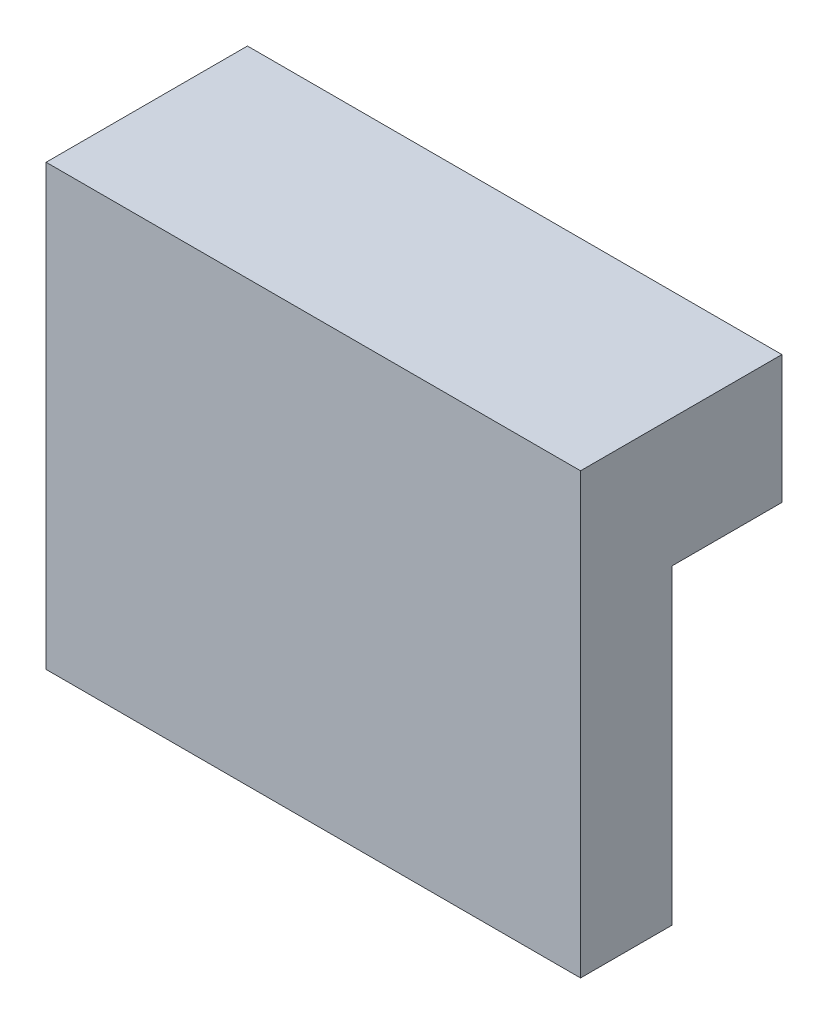
SolidWorks part; units mm, degrees
ref_plane "前视基准面" through (0, 0, 0) normal (0, 0, 1) x (1, 0, 0)
ref_plane "上视基准面" through (0, 0, 0) normal (0, 1, 0) x (1, 0, 0)
ref_plane "右视基准面" through (0, 0, 0) normal (1, 0, 0) x (0, 0, -1)
sketch "草图1" plane through (0, 0, 0) normal (0, 0, 1) x (1, 0, 0)
  line L1 (-73, 60) -> (73, 60)
  line L2 (-73, 60) -> (-73, -60)
  line L3 (-73, -60) -> (73, -60)
  line L4 (73, 60) -> (73, -60)
  line L5 (-73, 60) -> (73, -60) construction
  line L6 (-73, -60) -> (73, 60) construction
  point P0 (0, 0)
  dimension "D1" = 146
  dimension "D2" = 120
extrude "凸台-拉伸1" add sketch "草图1" along normal mid plane 25
sketch "草图2" plane through (0, 0, -12.5) normal (0, 0, -1) x (-1, 0, 0)
  line L0 (73, 60) -> (73, -60) construction
  line L1 (-73, 60) -> (73, 60)
  line L2 (-73, 60) -> (-73, 25)
  line L3 (-73, 25) -> (73, 25)
  line L4 (73, 60) -> (73, 25)
  dimension "D1" = 35
extrude "凸台-拉伸2" add sketch "草图2" along normal blind 30
equation "\"零件重量\"= \"SW-质量\""
